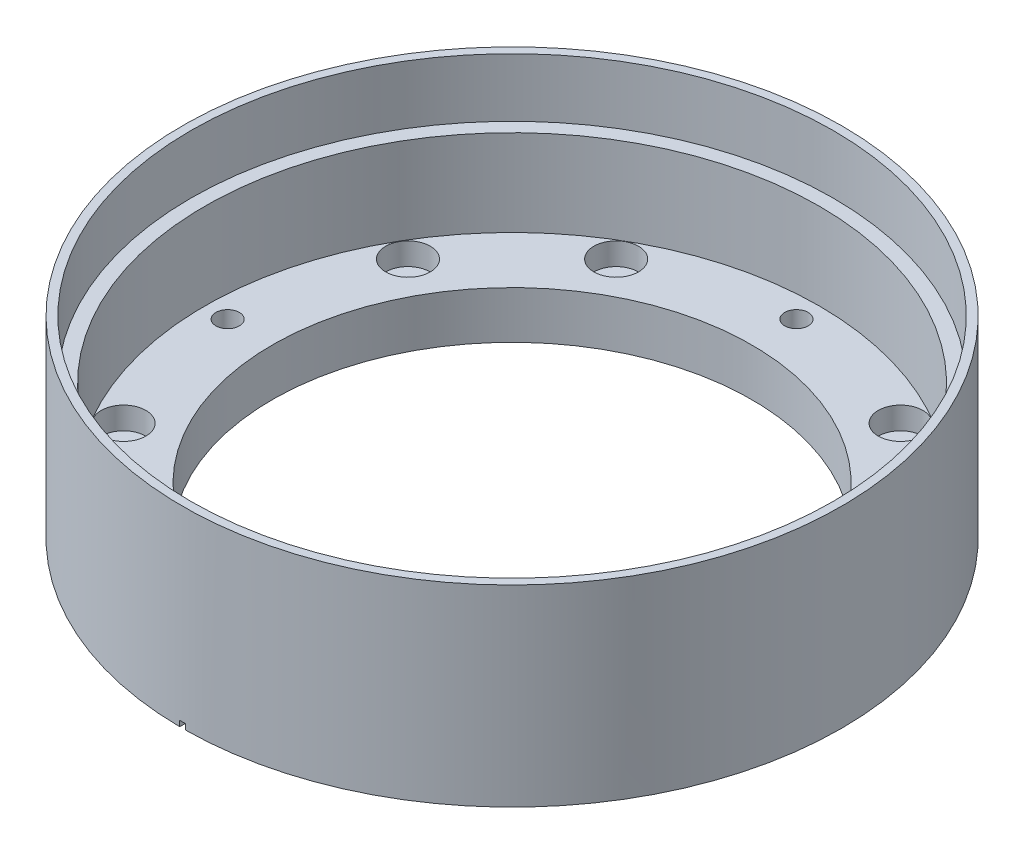
SolidWorks part; units mm, degrees
ref_plane "Front Plane" through (0, 0, 0) normal (0, 0, 1) x (1, 0, 0)
ref_plane "Top Plane" through (0, 0, 0) normal (0, 1, 0) x (1, 0, 0)
ref_plane "Right Plane" through (0, 0, 0) normal (1, 0, 0) x (0, 0, -1)
other "Configuration Table"
sketch "草图1" plane through (0, 0, 0) normal (0, 1, 0) x (1, 0, 0)
  circle A0 centre (0, 0) radius 59.5
extrude "凸台-拉伸1" add sketch "草图1" along normal blind 34.5
sketch "草图2" plane through (0, 34.5, 0) normal (0, 1, 0) x (1, 0, 0)
  circle A0 centre (0, 0) radius 57.6
extrude "切除-拉伸1" cut sketch "草图2" against normal blind 10.5
sketch "草图3" plane through (0, 24, 0) normal (0, 1, 0) x (1, 0, 0)
  circle A0 centre (0, 0) radius 55.1
extrude "切除-拉伸2" cut sketch "草图3" against normal blind 15.5
sketch "草图4" plane through (0, 8.5, 0) normal (0, 1, 0) x (1, 0, 0)
  circle A0 centre (0, 0) radius 43
extrude "切除-拉伸3" cut sketch "草图4" against normal through all
sketch "草图9" plane through (0, 8.5, 0) normal (0, 1, 0) x (1, 0, 0)
  line L0 (0, 0) -> (-44.1673, 25.5) construction
  circle A0 centre (-44.1673, 25.5) radius 4
  circle A1 centre (-25.5, 44.1673) radius 4
  circle A3 centre (25.5, 44.1673) radius 4
  circle A4 centre (44.1673, 25.5) radius 4
  circle A6 centre (44.1673, -25.5) radius 4
  circle A7 centre (25.5, -44.1673) radius 4
  circle A9 centre (-25.5, -44.1673) radius 4
  circle A10 centre (-44.1673, -25.5) radius 4
  circle A12 centre (0, 51) radius 4 [skipped]
  circle A13 centre (-51, 0) radius 4 [skipped]
  circle A14 centre (51, 0) radius 4 [skipped]
  circle A15 centre (0, -51) radius 4 [skipped]
  point P28 (0, 0)
  dimension "D1" = 12
extrude "切除-拉伸7" cut sketch "草图9" against normal blind 4
sketch "草图10" plane through (0, 8.5, 0) normal (0, 1, 0) x (1, 0, 0)
  line L0 (0, 0) -> (0, 51) construction
  circle A0 centre (0, 51) radius 2.1
  circle A1 centre (51, 0) radius 2.1
  circle A2 centre (0, -51) radius 2.1
  circle A3 centre (-51, 0) radius 2.1
  point P13 (0, 0)
  dimension "D1" = 4
extrude "切除-拉伸8" cut sketch "草图10" against normal through all
sketch "草图11" plane through (0, 0, 0) normal (0, -1, 0) x (1, 0, 0)
  line L0 (0, 51) -> (0, 0) construction
  circle A0 centre (0, 51) radius 3.75
  circle A1 centre (51, 0) radius 3.75
  circle A2 centre (0, -51) radius 3.75
  circle A3 centre (-51, 0) radius 3.75
  point P14 (0, 0)
  dimension "D1" = 4
extrude "切除-拉伸9" cut sketch "草图11" against normal blind 5
sketch "草图14" plane through (0, 0, 0) normal (0, -1, 0) x (1, 0, 0)
  circle A0 centre (0, 0) radius 59.1
  circle A1 centre (0, 0) radius 59.5
extrude "切除-拉伸12" cut sketch "草图14" against normal through all
sketch "草图15" plane through (0, 0, 0) normal (0, -1, 0) x (1, 0, 0)
  line L0 (0, 0) -> (0, -59.1) construction
  line L1 (0, -59.1) -> (0.5, -59.1)
  line L2 (0.5, -59.1) -> (0.5, -58.1)
  line L3 (0.5, -58.1) -> (-0.5, -58.1)
  line L4 (-0.5, -58.1) -> (-0.5, -59.1)
  line L5 (-0.5, -59.1) -> (0, -59.1)
  line L6 (0, 0) -> (7.981, 0) construction
  line L7 (0.5, 59.1) -> (0.5, 58.1)
  line L8 (0, 59.1) -> (0.5, 59.1)
  line L9 (-0.5, 59.1) -> (0, 59.1)
  line L10 (-0.5, 58.1) -> (-0.5, 59.1)
  line L11 (0.5, 58.1) -> (-0.5, 58.1)
  circle A0 centre (0, 0) radius 59.1 construction
extrude "切除-拉伸13" cut sketch "草图15" against normal blind 1
